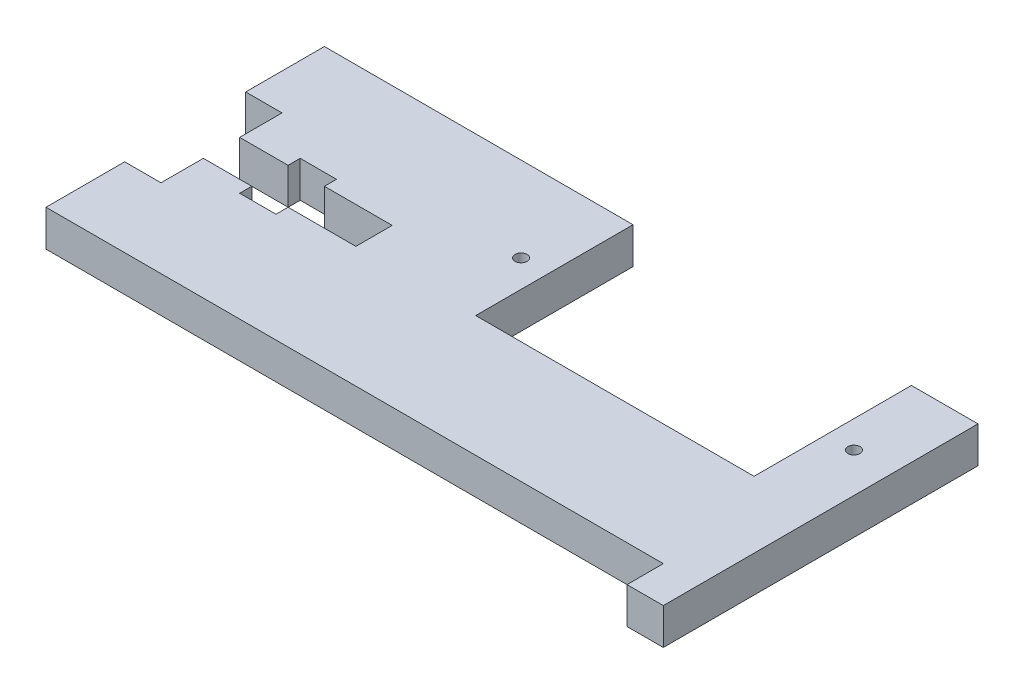
SolidWorks part; units mm, degrees
ref_plane "前视基准面" through (0, 0, 0) normal (0, 0, 1) x (1, 0, 0)
ref_plane "上视基准面" through (0, 0, 0) normal (0, 1, 0) x (1, 0, 0)
ref_plane "右视基准面" through (0, 0, 0) normal (1, 0, 0) x (0, 0, -1)
other "Configuration Table"
sketch "草图1" plane through (0, 0, 0) normal (0, 1, 0) x (1, 0, 0)
  line L0 (-45.9827, 0) -> (-45.9827, -6.5)
  line L1 (-45.9827, -6.5) -> (5.0173, -6.5)
  line L2 (5.0173, -6.5) -> (5.0173, -9.5)
  line L3 (5.0173, -9.5) -> (8.0173, -9.5)
  line L4 (8.0173, -9.5) -> (8.0173, 16.5)
  line L5 (8.0173, 16.5) -> (2.5173, 16.5)
  line L6 (2.5173, 16.5) -> (2.5173, 3.5)
  line L7 (2.5173, 3.5) -> (-20.4827, 3.5)
  line L8 (-20.4827, 3.5) -> (-20.4827, 16.5)
  line L9 (-20.4827, 16.5) -> (-45.9827, 16.5)
  line L10 (-45.9827, 16.5) -> (-45.9827, 10)
  line L11 (-45.9827, 10) -> (-42.9827, 10)
  line L12 (-42.9827, 10) -> (-42.9827, 6.5)
  line L13 (-42.9827, 6.5) -> (-38.9827, 6.5)
  line L14 (-38.9827, 6.5) -> (-38.9827, 7.5)
  line L15 (-38.9827, 7.5) -> (-35.9827, 7.5)
  line L16 (-35.9827, 7.5) -> (-35.9827, 6.5)
  line L17 (-35.9827, 6.5) -> (-30.3827, 6.5)
  line L18 (-30.3827, 6.5) -> (-30.3827, 3.5)
  line L19 (-30.3827, 5) -> (-44.8754, 5) construction
  line L20 (-35.9827, 3.5) -> (-30.3827, 3.5)
  line L21 (-35.9827, 2.5) -> (-35.9827, 3.5)
  line L22 (-38.9827, 3.5) -> (-38.9827, 2.5)
  line L23 (-38.9827, 2.5) -> (-35.9827, 2.5)
  line L24 (-42.9827, 3.5) -> (-38.9827, 3.5)
  line L25 (-42.9827, 0) -> (-42.9827, 3.5)
  line L26 (-45.9827, 0) -> (-42.9827, 0)
  line L27 (-0.5222, 3.5) -> (-0.5222, 9.5) construction
  line L28 (2.5173, 9.5) -> (4.7673, 9.5) construction
  line L29 (4.7673, 9.5) -> (-22.7327, 9.5) construction
  circle A0 centre (-22.7327, 9.5) radius 0.5
  circle A1 centre (4.7673, 9.5) radius 0.5
extrude "凸台-拉伸1" add sketch "草图1" along normal blind 3
